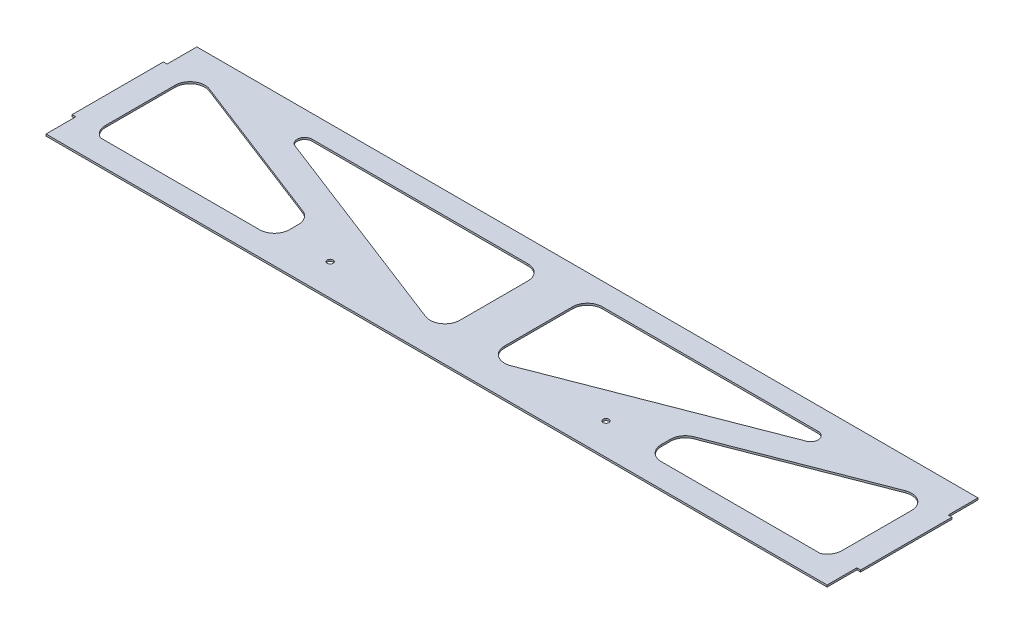
SolidWorks part; units mm, degrees
material "Balsa"
ref_plane "Front Plane" through (0, 0, 0) normal (0, 0, 1) x (1, 0, 0)
ref_plane "Top Plane" through (0, 0, 0) normal (0, 1, 0) x (1, 0, 0)
ref_plane "Right Plane" through (0, 0, 0) normal (1, 0, 0) x (0, 0, -1)
sketch "Sketch1" plane through (0, 0, 0) normal (0, 1, 0) x (1, 0, 0)
  line L0 (-333.375, 38.989) -> (-333.375, 64.389)
  line L1 (-333.375, -64.389) -> (333.375, -64.389)
  line L2 (-333.375, -64.389) -> (-333.375, -38.989)
  line L3 (-333.375, 64.389) -> (333.375, 64.389)
  line L4 (333.375, -64.389) -> (333.375, -38.989)
  line L5 (-333.375, -64.389) -> (333.375, 64.389) construction
  line L6 (-333.375, 64.389) -> (333.375, -64.389) construction
  line L7 (-333.375, 38.989) -> (-336.55, 38.989)
  line L9 (-333.375, -38.989) -> (-336.55, -38.989)
  line L10 (-336.55, 38.989) -> (-336.55, -38.989)
  line L12 (0, -1000) -> (0, 49000) construction
  line L13 (333.375, -38.989) -> (336.55, -38.989)
  line L14 (336.55, 38.989) -> (336.55, -38.989)
  line L15 (333.375, 38.989) -> (336.55, 38.989)
  line L16 (333.375, 38.989) -> (333.375, 64.389)
  point P0 (0, 0)
  dimension "D1" = 128.778
  dimension "D2" = 666.75
  dimension "D3" = 3.175
  dimension "D4" = 25.4
  dimension "D5" = 25.4
extrude "Boss-Extrude1" add sketch "Sketch1" along normal blind 1.5875
sketch "Sketch3" plane through (0, 1.5875, 0) normal (0, 1, 0) x (1, 0, 0)
  line L0 (-1000, 0) -> (49000, 0) construction
  line L1 (0, -1000) -> (0, 49000) construction
  line L2 (-314.325, 26.8088) -> (-314.325, -32.639)
  line L5 (-215.9695, 45.339) -> (-31.75, 45.339)
  line L6 (-19.05, 32.639) -> (-19.05, -25.468)
  line L7 (-36.3321, -37.3126) -> (-218.2606, 33.0667)
  line L8 (-333.375, 64.389) -> (-333.375, 38.989) construction
  line L10 (333.375, 64.389) -> (-333.375, 64.389) construction
  line L11 (36.3321, -37.3126) -> (218.2606, 33.0667)
  line L12 (19.05, 32.639) -> (19.05, -25.468)
  line L13 (215.9695, 45.339) -> (31.75, 45.339)
  line L16 (314.325, 26.8088) -> (314.325, -32.639)
  line L25 (307.3046, -43.9982) -> (171.45, -43.9982)
  line L26 (297.0429, 38.6534) -> (166.8679, -11.705)
  line L27 (158.75, -31.2982) -> (158.75, -23.5496)
  line L28 (-307.3046, -43.9982) -> (-171.45, -43.9982)
  line L29 (-297.0429, 38.6534) -> (-166.8679, -11.705)
  line L30 (-158.75, -23.5496) -> (-158.75, -31.2982)
  arc A0 (-19.05, -25.468) -> (-36.3321, -37.3126) centre (-31.75, -25.468) cw
  arc A1 (-31.75, 45.339) -> (-19.05, 32.639) centre (-31.75, 32.639) cw
  arc A2 (-314.325, -32.639) -> (-307.3046, -43.9982) centre (-301.625, -32.639) ccw
  arc A3 (-314.325, 26.8088) -> (-297.0429, 38.6534) centre (-301.625, 26.8088) cw
  arc A4 (-215.9695, 45.339) -> (-218.2606, 33.0667) centre (-215.9695, 38.989) ccw
  arc A7 (215.9695, 45.339) -> (218.2606, 33.0667) centre (215.9695, 38.989) cw
  arc A8 (314.325, 26.8088) -> (297.0429, 38.6534) centre (301.625, 26.8088) ccw
  arc A9 (314.325, -32.639) -> (307.3046, -43.9982) centre (301.625, -32.639) cw
  arc A10 (31.75, 45.339) -> (19.05, 32.639) centre (31.75, 32.639) ccw
  arc A11 (19.05, -25.468) -> (36.3321, -37.3126) centre (31.75, -25.468) ccw
  arc A17 (158.75, -23.5496) -> (166.8679, -11.705) centre (171.45, -23.5496) cw
  arc A18 (158.75, -31.2982) -> (171.45, -43.9982) centre (171.45, -31.2982) ccw
  arc A19 (-158.75, -23.5496) -> (-166.8679, -11.705) centre (-171.45, -23.5496) ccw
  arc A20 (-158.75, -31.2982) -> (-171.45, -43.9982) centre (-171.45, -31.2982) cw
  point P15 (-333.375, 51.689)
  point P22 (-19.05, -43.9982)
  point P27 (-323.85, -43.9982)
  point P30 (-323.85, 45.339)
  point P33 (-249.9841, 45.339)
  point P54 (249.9841, 45.339)
  point P55 (323.85, 45.339)
  point P56 (323.85, -43.9982)
  point P57 (19.05, -43.9982)
  dimension "D6" = 12.7
  dimension "D7" = 6.35
  dimension "D2" = 12.7
  dimension "D5" = 12.7
  dimension "D1" = 19.05
  dimension "D3" = 19.05
  dimension "D4" = 19.05
extrude "Cut-Extrude2" cut sketch "Sketch3" against normal through all
sketch "Sketch4" plane through (0, 1.5875, 0) normal (0, 1, 0) x (1, 0, 0)
  line L0 (-333.375, -64.389) -> (333.375, -64.389) construction
  line L1 (-333.375, -38.989) -> (-333.375, -64.389) construction
  line L2 (0, -935.611) -> (0, 49064.389) construction
  line L3 (333.375, 64.389) -> (-333.375, 64.389) construction
  circle A0 centre (-117.729, -37.465) radius 2.5
  circle A2 centre (117.729, -37.465) radius 2.5
  point P12 (0, 64.389)
  dimension "D1" = 5
  dimension "D3" = 26.924
  dimension "D4" = 215.646
extrude "Cut-Extrude3" cut sketch "Sketch4" against normal through all
